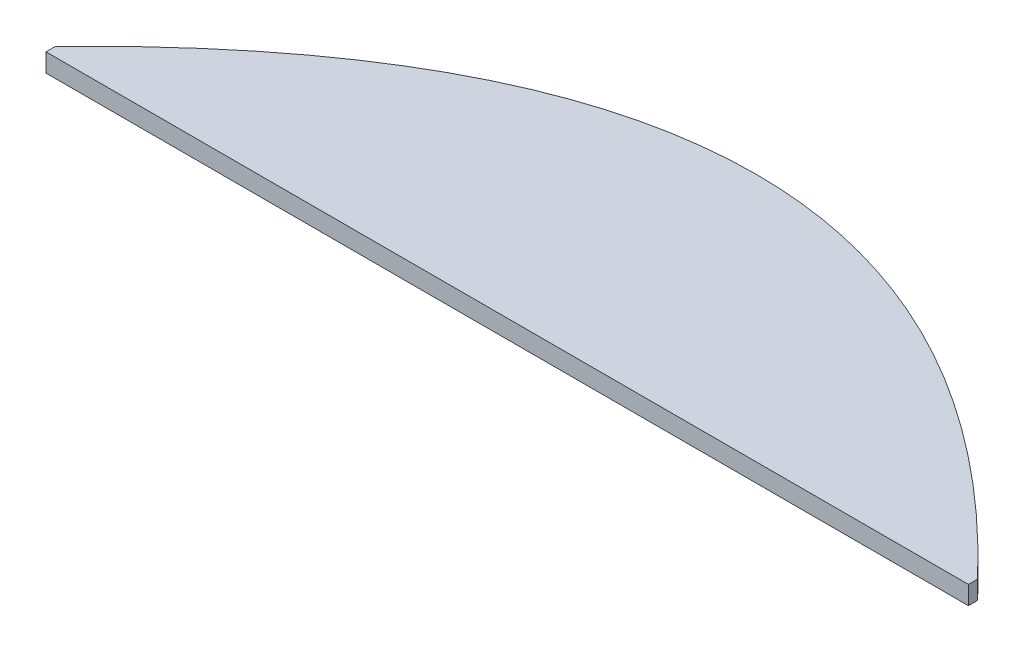
SolidWorks part; units mm, degrees
ref_plane "前视" through (0, 0, 0) normal (0, 0, 1) x (1, 0, 0)
ref_plane "上视" through (0, 0, 0) normal (0, 1, 0) x (1, 0, 0)
ref_plane "右视" through (0, 0, 0) normal (1, 0, 0) x (0, 0, -1)
sketch "草图1" plane through (0, 0, 0) normal (0, 1, 0) x (1, 0, 0)
  line L0 (0, 0) -> (-250, 0)
  line L1 (0, 0) -> (250, 0)
  spline S0 degree 2 poles (-250, 0) (0, 260) (250, 0) knots 0 0 0 1 1 1
sketch3d "URDF Reference"
  line L0 (0, 0, 0) -> (10, 0, 0) construction
  line L1 (0, 0, 0) -> (0, 0, -10) construction
  point P0 (0, 0, 0)
  point P1 (0, 0, 0)
extrude "凸台-拉伸3" add sketch "草图1" along normal blind 5
sketch "草图3" plane through (0, 0, 0) normal (0, -1, 0) x (1, 0, 0)
  line L0 (-250, 0) -> (250, 0)
  parabola Q0 (250, 0) -> (-250, 0) focus (0, -9.8077) apex (0, -130) construction
  spline S0 degree 2 poles (-250, 0) (0, -260) (250, 0) knots 0 0 0 1 1 1
extrude "凸台-拉伸4" add sketch "草图3" along normal blind 5
sketch "草图4" plane through (0, 0, 0) normal (0, 0, 1) x (1, 0, 0)
  line L1 (-250, 5) -> (250, 5)
  line L2 (-250, 5) -> (-250, -5)
  line L3 (-250, -5) -> (250, -5)
  line L4 (250, 5) -> (250, -5)
extrude "凸台-拉伸5" add sketch "草图4" along normal blind 5
